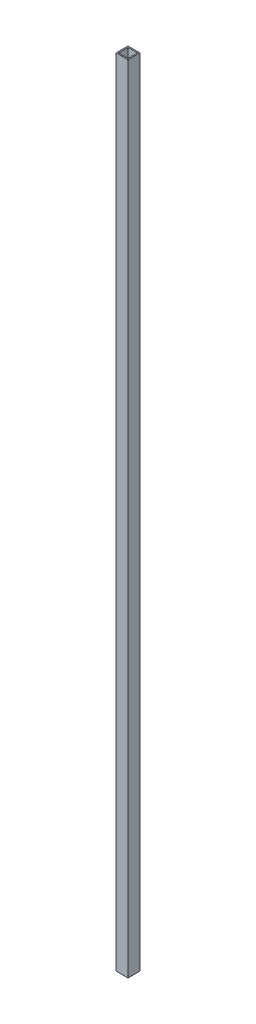
SolidWorks part; units mm, degrees
material "pullwinding"
ref_plane "Płaszczyzna przednia" through (0, 0, 0) normal (0, 0, 1) x (1, 0, 0)
ref_plane "Płaszczyzna górna" through (0, 0, 0) normal (0, 1, 0) x (1, 0, 0)
ref_plane "Płaszczyzna prawa" through (0, 0, 0) normal (1, 0, 0) x (0, 0, -1)
sketch "Sketch1" plane through (0, 0, 0) normal (0, 1, 0) x (1, 0, 0)
  line L0 (1.5, 1.5) -> (1.5, 13.5)
  line L1 (0, 0) -> (15, 0)
  line L2 (0, 0) -> (0, 15)
  line L3 (0, 15) -> (15, 15)
  line L4 (15, 0) -> (15, 15)
  line L5 (1.5, 13.5) -> (13.5, 13.5)
  line L6 (13.5, 1.5) -> (13.5, 13.5)
  line L7 (1.5, 1.5) -> (13.5, 1.5)
  dimension "D1" = 15
  dimension "D2" = 15
  dimension "D3" = 1.5
extrude "Boss-Extrude1" add sketch "Sketch1" along normal blind 1000
